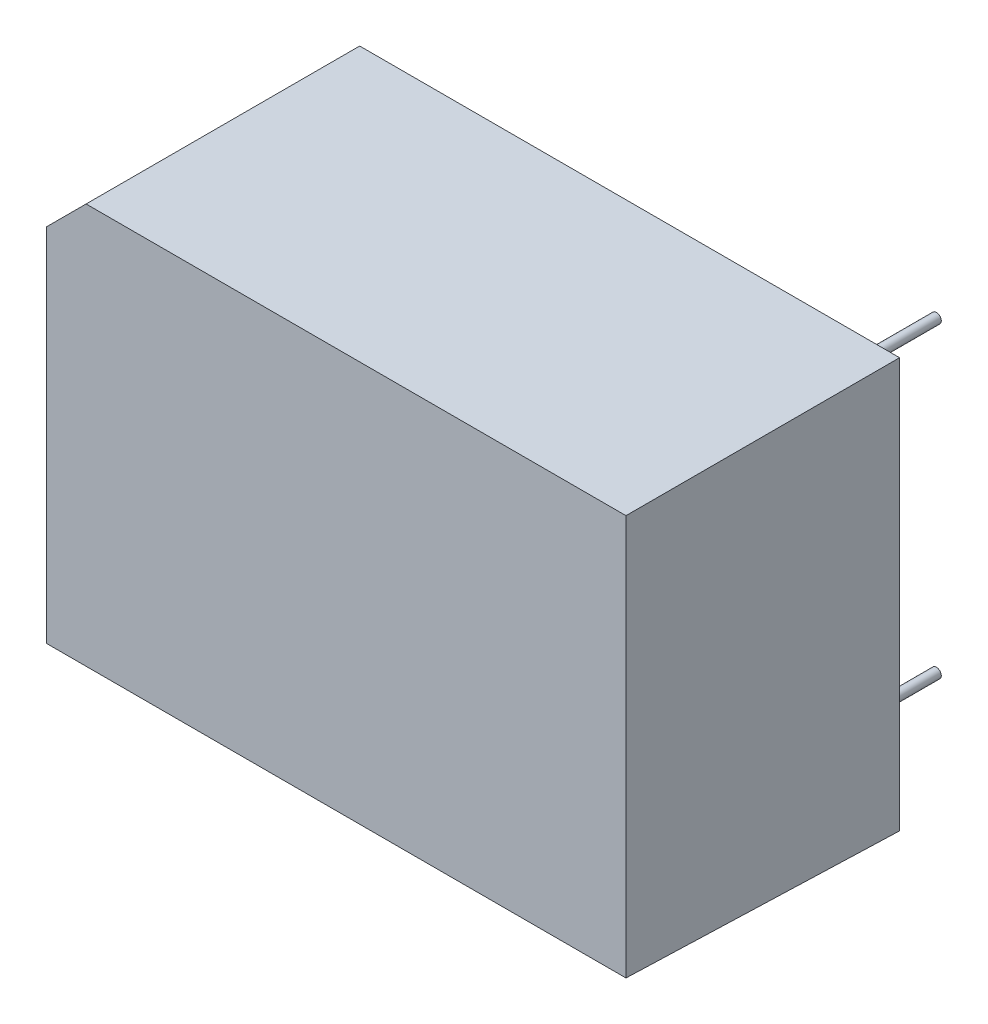
SolidWorks part; units mm, degrees
ref_plane "Front Plane" through (0, 0, 0) normal (0, 0, 1) x (1, 0, 0)
ref_plane "Top Plane" through (0, 0, 0) normal (0, 1, 0) x (1, 0, 0)
ref_plane "Right Plane" through (0, 0, 0) normal (1, 0, 0) x (0, 0, -1)
sketch "Sketch2" plane through (0, 0, 0) normal (0, 0, 1) x (1, 0, 0)
  line L0 (-22.987, -16.002) -> (22.987, 16.002) construction
  line L1 (-22.987, 16.002) -> (22.987, 16.002)
  line L2 (-22.987, 16.002) -> (-22.987, -16.002)
  line L3 (-22.987, -16.002) -> (22.987, -16.002)
  line L4 (22.987, 16.002) -> (22.987, -16.002)
  point P4 (0, 0)
  dimension "D1" = 45.974
  dimension "D2" = 32.004
extrude "Boss-Extrude1" add sketch "Sketch2" along normal blind 21 draft 1
sketch "Sketch4" plane through (0, 0, 21) normal (0, 0, 1) x (1, 0, 0)
  line L0 (-19.177, 16.002) -> (-22.987, 16.002)
  line L1 (22.987, 16.002) -> (-22.987, 16.002) construction
  line L2 (-22.987, 16.002) -> (-22.987, 12.192)
  line L3 (-22.987, 16.002) -> (-22.987, -16.002) construction
  line L4 (-22.987, 12.192) -> (-19.177, 16.002)
  dimension "D1" = 45
  dimension "D2" = 3.81
extrude "Cut-Extrude1" cut sketch "Sketch4" against normal through all
sketch "Sketch3" plane through (0, 0, 0) normal (0, 0, -1) x (-1, 0, 0)
  line L0 (-17.737, 16.002) -> (-17.737, -16.002) construction
  line L1 (-22.987, 16.002) -> (19.177, 16.002) construction
  line L2 (22.987, -16.002) -> (-22.987, -16.002) construction
  line L3 (17.763, 16.002) -> (17.763, -16.002) construction
  line L4 (-22.987, -16.002) -> (-22.987, 16.002) construction
  line L5 (22.987, -12.002) -> (-22.987, -12.002) construction
  line L6 (22.987, 12.192) -> (22.987, -16.002) construction
  circle A0 centre (-17.737, 11.998) radius 0.381
  circle A1 centre (17.763, 3.998) radius 0.381
  circle A2 centre (17.763, -12.002) radius 0.381
  circle A3 centre (-17.737, -12.002) radius 0.381
  dimension "D1" = 0.762
  dimension "D4" = 24
  dimension "D5" = 16
  dimension "D6" = 4
  dimension "D2" = 5.25
  dimension "D3" = 35.5
extrude "Boss-Extrude2" add sketch "Sketch3" along normal blind 8.128
